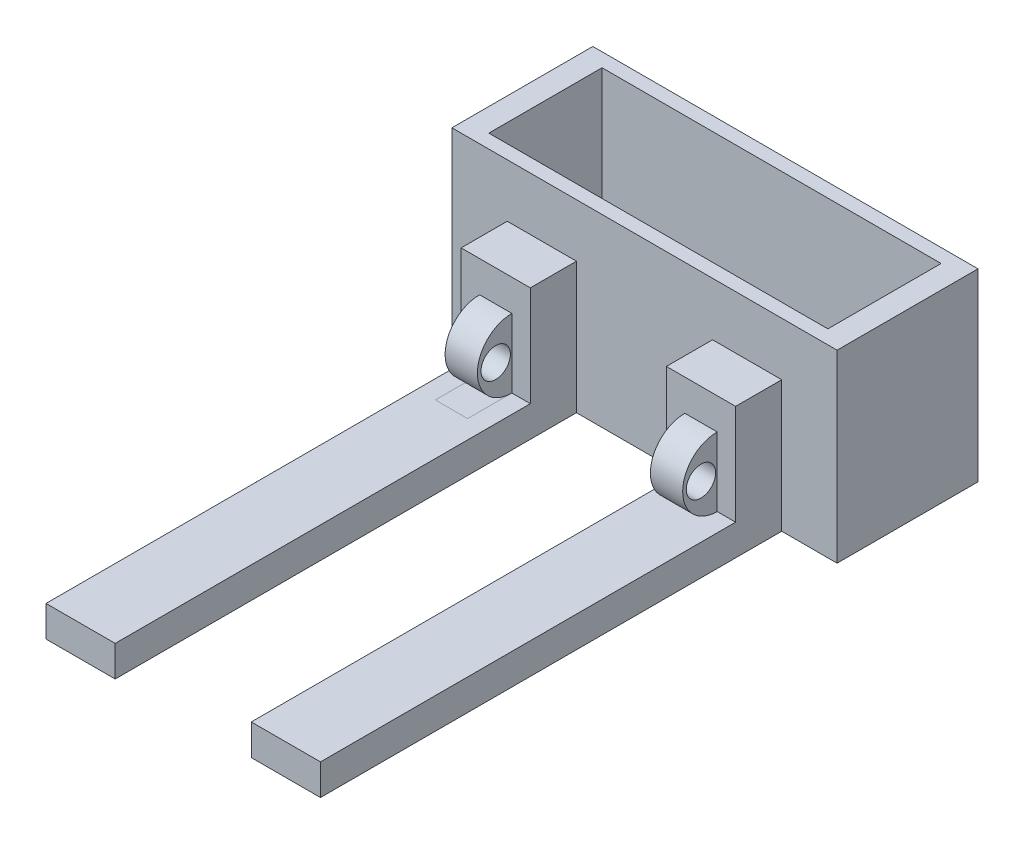
SolidWorks part; units mm, degrees
ref_plane "Front Plane" through (0, 0, 0) normal (0, 0, 1) x (1, 0, 0)
ref_plane "Top Plane" through (0, 0, 0) normal (0, 1, 0) x (1, 0, 0)
ref_plane "Right Plane" through (0, 0, 0) normal (1, 0, 0) x (0, 0, -1)
sketch "Sketch1" plane through (0, 0, 0) normal (0, 0, 1) x (1, 0, 0)
  line L1 (-53.025, 25.4) -> (53.025, 25.4)
  line L2 (-53.025, 25.4) -> (-53.025, -25.4)
  line L3 (-53.025, -25.4) -> (53.025, -25.4)
  line L4 (53.025, 25.4) -> (53.025, -25.4)
  line L5 (-53.025, 25.4) -> (53.025, -25.4) construction
  line L6 (-53.025, -25.4) -> (53.025, 25.4) construction
  point P0 (0, 0)
  dimension "D1" = 106.05
  dimension "D2" = 50.8
extrude "Boss-Extrude1" add sketch "Sketch1" along normal blind 38.8
sketch "Sketch3" plane through (0, 25.4, 0) normal (0, 1, 0) x (1, 0, 0)
  line L0 (-46.675, -3.81) -> (-46.675, -34.99)
  line L1 (-46.675, -34.99) -> (46.675, -34.99)
  line L2 (46.675, -34.99) -> (46.675, -3.81)
  line L3 (46.675, -3.81) -> (-46.675, -3.81)
  line L4 (-53.025, -38.8) -> (-53.025, 0) construction
  line L5 (53.025, -38.8) -> (53.025, 0) construction
  line L6 (53.025, 0) -> (-53.025, 0) construction
  line L7 (53.025, -38.8) -> (-53.025, -38.8) construction
  dimension "D1" = 6.35
  dimension "D2" = 6.35
  dimension "D3" = 3.81
  dimension "D4" = 3.81
extrude "Cut-Extrude1" cut sketch "Sketch3" against normal blind 64.516 contours L3 L0 L1 L2
sketch "Sketch7" plane through (0, 0, 38.8) normal (0, 0, 1) x (1, 0, 0)
  line L0 (-53.025, -25.4) -> (53.025, -25.4) construction
  line L1 (-37.785, -25.4) -> (-18.735, -25.4)
  line L6 (37.785, -25.4) -> (18.735, -25.4)
  line L12 (-37.785, -25.4) -> (-18.735, -25.4)
  line L13 (-37.785, -25.4) -> (-37.785, -21.6347)
  line L15 (-18.735, -25.4) -> (-18.735, -21.6347)
  line L16 (18.735, -25.4) -> (37.785, -25.4)
  line L17 (18.735, -25.4) -> (18.735, -21.6347)
  line L19 (37.785, -25.4) -> (37.785, -21.6347)
  line L20 (-37.785, -25.4) -> (-18.735, -25.4)
  line L21 (-37.785, -25.4) -> (-37.785, -8.3855)
  line L22 (-37.785, -8.3855) -> (-18.735, -8.3855)
  line L23 (-18.735, -25.4) -> (-18.735, -8.3855)
  line L24 (18.735, -25.4) -> (37.785, -25.4)
  line L25 (18.735, -25.4) -> (18.735, -8.382)
  line L26 (18.735, -8.382) -> (37.785, -8.382)
  line L27 (37.785, -25.4) -> (37.785, -8.382)
  line M12 (-53.025, -25.4) -> (53.025, -25.4)
  dimension "D1" = 17.0145
  dimension "D2" = 17.018
  dimension "D3" = 19.05
extrude "Boss-Extrude2" add sketch "Sketch7" along normal blind 12.7 contours L15 L23 L22 L21 L13 M12 | L19 L27 L26 L25 L17 M12
sketch "Sketch8" plane through (0, 0, 51.5) normal (0, 0, 1) x (1, 0, 0)
  line L0 (-18.735, -25.4) -> (-18.735, -8.3855) construction
  line L1 (-37.785, -25.4) -> (-18.735, -25.4)
  line L2 (-37.785, -25.4) -> (-37.785, -16.8928)
  line L3 (-37.785, -16.8928) -> (-18.735, -16.8928)
  line L4 (-18.735, -25.4) -> (-18.735, -16.8928)
  line L5 (37.785, -25.4) -> (37.785, -8.382) construction
  line L6 (18.735, -25.4) -> (37.785, -25.4)
  line L7 (18.735, -25.4) -> (18.735, -16.891)
  line L8 (18.735, -16.891) -> (37.785, -16.891)
  line L9 (37.785, -25.4) -> (37.785, -16.891)
extrude "Boss-Extrude3" add sketch "Sketch8" along normal blind 114.3
sketch "Sketch9" plane through (0, 0, 38.8) normal (0, 0, 1) x (1, 0, 0)
  line L1 (-37.785, -8.3855) -> (-18.735, -8.3855)
  line L2 (-37.785, -8.3855) -> (-37.785, 10.7335)
  line L3 (-37.785, 10.7335) -> (-18.735, 10.7335)
  line L4 (-18.735, -8.3855) -> (-18.735, 10.7335)
  line L5 (18.735, -8.382) -> (37.785, -8.382)
  line L6 (18.735, -8.382) -> (18.735, 10.7335)
  line L7 (18.735, 10.7335) -> (37.785, 10.7335)
  line L8 (37.785, -8.382) -> (37.785, 10.7335)
extrude "Boss-Extrude4" add sketch "Sketch9" along normal blind 12.7
sketch "Sketch10" plane through (0, 0, 51.5) normal (0, 0, 1) x (1, 0, 0)
  line L0 (-18.735, -16.8928) -> (-37.785, -16.8928) construction
  line L1 (-32.705, -16.8928) -> (-23.815, -16.8928)
  line L2 (-32.705, -16.8928) -> (-32.705, 2.0964)
  line L3 (-32.705, 2.0964) -> (-23.815, 2.0964)
  line L4 (-23.815, -16.8928) -> (-23.815, 2.0964)
  line L5 (37.785, -16.891) -> (18.735, -16.891) construction
  line L6 (23.815, -16.891) -> (32.705, -16.891)
  line L7 (23.815, -16.891) -> (23.815, 2.0964)
  line L8 (23.815, 2.0964) -> (32.705, 2.0964)
  line L9 (32.705, -16.891) -> (32.705, 2.0964)
  line L10 (-37.785, -25.4) -> (-37.785, 10.7335) construction
  line L11 (-18.735, -25.4) -> (-18.735, 10.7335) construction
  line L12 (18.735, -16.891) -> (18.735, 10.7335) construction
  line L13 (37.785, -25.4) -> (37.785, 10.7335) construction
  dimension "D1" = 5.08
  dimension "D2" = 5.08
  dimension "D3" = 5.08
  dimension "D4" = 5.08
extrude "Boss-Extrude5" add sketch "Sketch10" along normal blind 12.192
sketch "Sketch11" plane through (32.705, 0, 0) normal (1, 0, 0) x (0, 0, -1)
  line L0 (-51.5, -16.891) -> (-51.5, 2.0964) construction
  line L1 (-63.692, 2.0964) -> (-51.5, 2.0964) construction
  line L2 (-51.5, 2.0964) -> (-51.5, -16.891)
  arc A0 (-51.5, -16.891) -> (-51.5, 2.0964) centre (-51.5, -7.3973) cw
  line M2 (-51.5, 2.0964) -> (-63.692, 2.0964)
  line M3 (-63.692, 2.0964) -> (-63.692, -16.891)
  line M4 (-63.692, -16.891) -> (-51.5, -16.891)
extrude "Cut-Extrude7" cut sketch "Sketch11" against normal blind 78.232 contours A0 M4 M2 M3
sketch "Sketch13" plane through (32.705, 0, 0) normal (1, 0, 0) x (0, 0, -1)
  circle A0 centre (-55.9589, -7.3973) radius 4.044
  dimension "D1" = 8.0881
extrude "Cut-Extrude9" cut sketch "Sketch13" against normal blind 83.82
